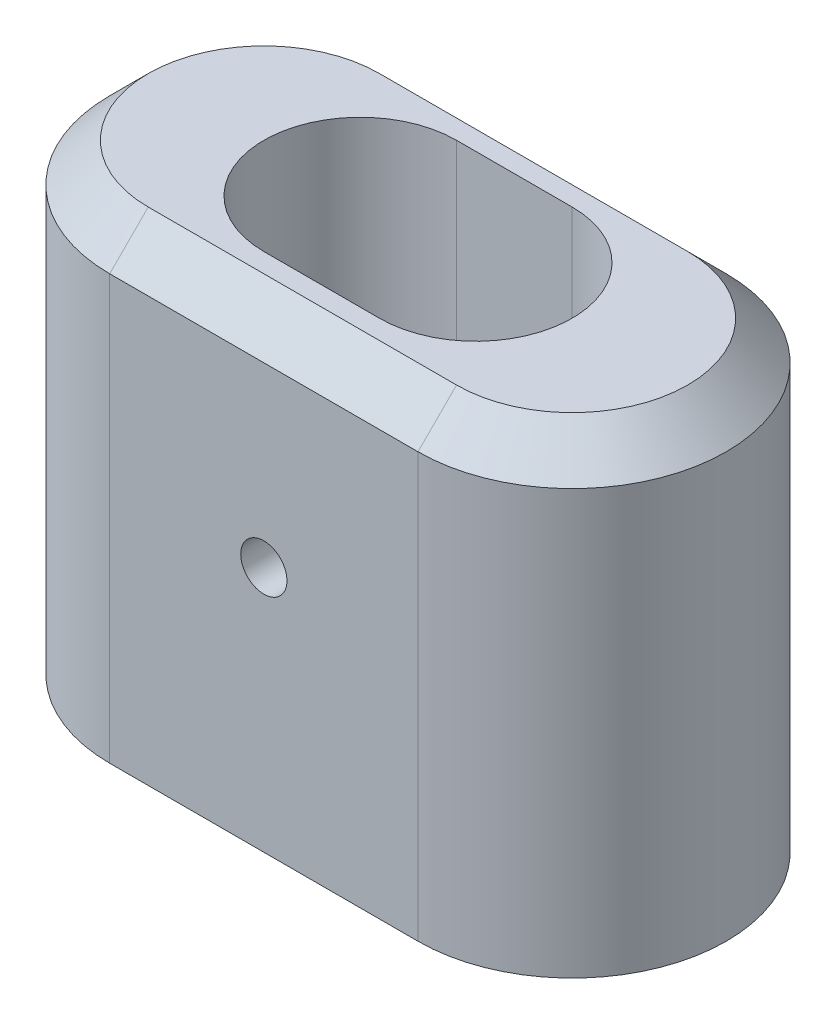
SolidWorks part; units mm, degrees
ref_plane "Front Plane" through (0, 0, 0) normal (0, 0, 1) x (1, 0, 0)
ref_plane "Top Plane" through (0, 0, 0) normal (0, 1, 0) x (1, 0, 0)
ref_plane "Right Plane" through (0, 0, 0) normal (1, 0, 0) x (0, 0, -1)
sketch "Sketch2" plane through (0, 0, 0) normal (0, 1, 0) x (1, 0, 0)
  line L0 (-40, 0) -> (0, 0) construction
  line L1 (-20, 20) -> (20, 20)
  line L2 (-20, -20) -> (20, -20)
  line L3 (0, 0) -> (40, 0) construction
  line L4 (7.5, 12.5) -> (-7.5, 12.5)
  line L6 (7.5, -12.5) -> (-7.5, -12.5)
  line L8 (0, 20) -> (0, 0) construction
  line L9 (0, 0) -> (0, -20) construction
  arc A0 (-20, 20) -> (-20, -20) centre (-20, 0) ccw
  arc A1 (20, -20) -> (20, 20) centre (20, 0) ccw
  arc A2 (-7.5, 12.5) -> (-7.5, -12.5) centre (-7.5, 0) ccw
  arc A5 (7.5, -12.5) -> (7.5, 12.5) centre (7.5, 0) ccw
  point P0 (0, 0)
  point P4 (0, 0)
  dimension "D1" = 40
  dimension "D2" = 40
  dimension "D3" = 20
  dimension "D6" = 20
  dimension "D7" = 12.5
  dimension "D4" = 12.5
  dimension "D5" = 25
  dimension "D8" = 15
extrude "Boss-Extrude1" add sketch "Sketch2" along normal blind 60
chamfer "Chamfer1" distance 5 angle 45 4 edges at (0, 60, -20) (-40, 60, 0) (40, 60, 0) (0, 60, 20)
sketch "Sketch3" plane through (0, 0, -20) normal (0, 0, -1) x (-1, 0, 0)
  line L0 (0, 60) -> (0, 32) construction
  line L1 (-20, 60) -> (20, 60) construction
  circle A0 centre (0, 32) radius 3
  dimension "D2" = 6
  dimension "D1" = 28
extrude "Cut-Extrude1" cut sketch "Sketch3" against normal through all contours A0
